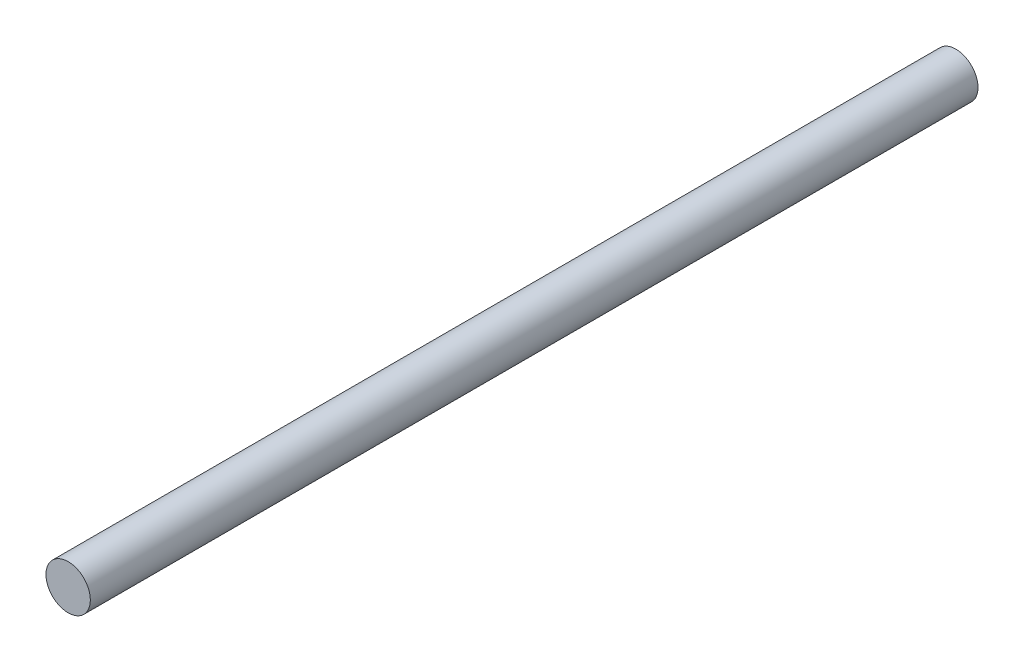
SolidWorks part; units mm, degrees
ref_plane "Front Plane" through (0, 0, 0) normal (0, 0, 1) x (1, 0, 0)
ref_plane "Top Plane" through (0, 0, 0) normal (0, 1, 0) x (1, 0, 0)
ref_plane "Right Plane" through (0, 0, 0) normal (1, 0, 0) x (0, 0, -1)
sketch "Sketch3" plane through (0, 0, 0) normal (0, 0, 1) x (1, 0, 0)
  circle A0 centre (0, 0) radius 40
  dimension "D1" = 80
extrude "Boss-Extrude3" add sketch "Sketch3" against normal blind 1600
